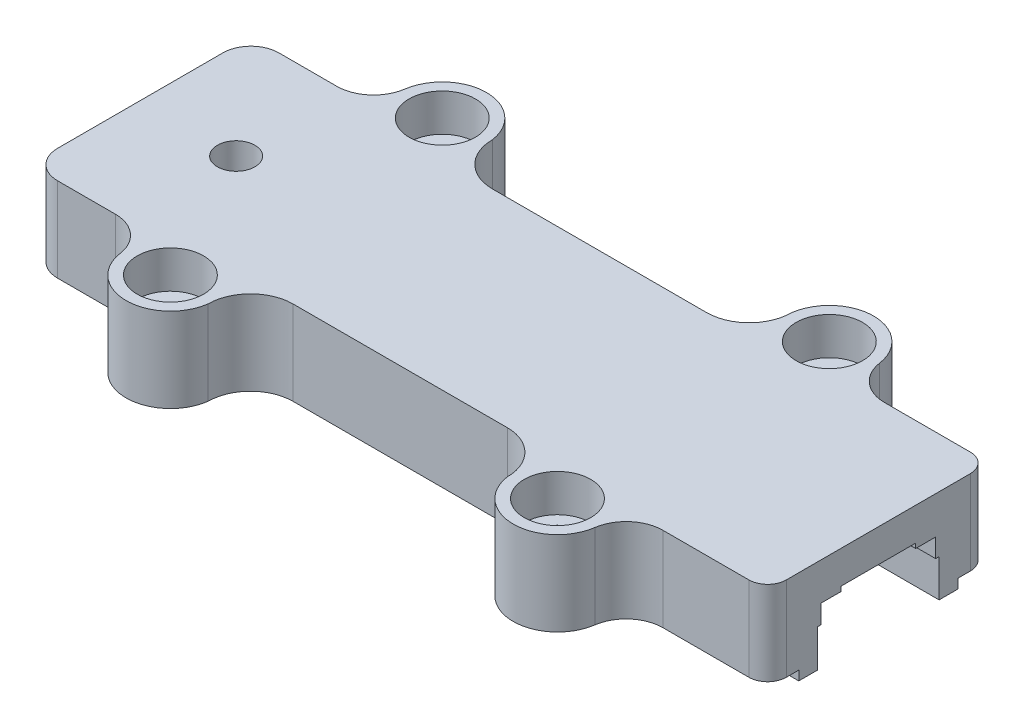
SolidWorks part; units mm, degrees
ref_plane "Front Plane" through (0, 0, 0) normal (0, 0, 1) x (1, 0, 0)
ref_plane "Top Plane" through (0, 0, 0) normal (0, 1, 0) x (1, 0, 0)
ref_plane "Right Plane" through (0, 0, 0) normal (1, 0, 0) x (0, 0, -1)
sketch "Sketch1" plane through (0, 0, 0) normal (0, 1, 0) x (1, 0, 0)
  line L1 (0, 15) -> (100, 15)
  line L2 (0, 15) -> (0, -15)
  line L3 (0, -15) -> (100, -15)
  line L4 (100, 15) -> (100, -15)
  point P4 (0, 0)
  dimension "D1" = 30
  dimension "D2" = 100
extrude "Boss-Extrude1" add sketch "Sketch1" along normal blind 12.7
sketch "Sketch2" plane through (100, 0, 0) normal (1, 0, 0) x (0, 0, -1)
  line L1 (-7.6, 0) -> (7.6, 0)
  line L2 (-7.6, 0) -> (-7.6, 7.62)
  line L3 (-7.6, 7.62) -> (7.6, 7.62)
  line L4 (7.6, 0) -> (7.6, 7.62)
  point P4 (0, 0)
  dimension "D1" = 15.2
  dimension "D2" = 7.62
extrude "Cut-Extrude1" cut sketch "Sketch2" against normal through all
sketch "Sketch3" plane through (100, 0, 0) normal (1, 0, 0) x (0, 0, -1)
  line L1 (-15, 0) -> (-7.6, 0) construction
  line L2 (7.6, 0) -> (15, 0) construction
  line L3 (-7.6, 0) -> (-8.235, 0)
  line L10 (7.6, 0) -> (7.6, 7.62) construction
  line L12 (7.6, 7.62) -> (-7.6, 7.62) construction
  line L13 (-7.6, 0) -> (-8.235, 0)
  line L14 (-7.6, 0) -> (-7.6, 5.08)
  line L15 (-7.6, 5.08) -> (-8.235, 5.08)
  line L16 (-8.235, 0) -> (-8.235, 5.08)
  line L17 (-7.6, 7.62) -> (-7.6, 0) construction
  line L18 (7.6, 0) -> (8.235, 0)
  line L19 (7.6, 0) -> (7.6, 5.08)
  line L20 (7.6, 5.08) -> (8.235, 5.08)
  line L21 (8.235, 0) -> (8.235, 5.08)
  line L22 (-5.06, 7.62) -> (5.06, 7.62)
  line L23 (-5.06, 7.62) -> (-5.06, 8.255)
  line L24 (-5.06, 8.255) -> (5.06, 8.255)
  line L25 (5.06, 7.62) -> (5.06, 8.255)
  line M1 (-15, 0) -> (-7.6, 0)
  line M2 (-7.6, 0) -> (-7.6, 7.62)
  line M3 (-7.6, 7.62) -> (7.6, 7.62)
  line M4 (7.6, 7.62) -> (7.6, 0)
  line M5 (7.6, 0) -> (15, 0)
  dimension "D5" = 0.635
  dimension "D6" = 2.54
  dimension "D7" = 0.635
  dimension "D8" = 2.54
  dimension "D9" = 0.635
  dimension "D10" = 2.54
  dimension "D11" = 2.54
extrude "Cut-Extrude2" cut sketch "Sketch3" against normal through all contours L16 L15 M1 M2 | L25 L24 L23 M3 | L21 L20 M5 M4
sketch "Sketch4" plane through (0, 0, 0) normal (0, -1, 0) x (1, 0, 0)
  line L1 (0, -8.235) -> (5, -8.235)
  line L2 (0, -8.235) -> (0, 8.235)
  line L3 (0, 8.235) -> (5, 8.235)
  line L4 (5, -8.235) -> (5, 8.235)
  line L5 (0, -8.235) -> (100, -8.235) construction
  line L6 (0, 8.235) -> (100, 8.235) construction
  dimension "D1" = 5
extrude "Boss-Extrude2" add sketch "Sketch4" against normal up to next
fillet "Fillet7" radius 1.5875 2 edges at (5, 6.35, -7.6) (5, 6.35, 7.6)
fillet "Fillet8" radius 1.5875 2 edges at (5, 2.54, -8.235) (5, 2.54, 8.235)
sketch "Sketch9" plane through (0, 7.62, 0) normal (0, -1, 0) x (1, 0, 0)
  line L0 (5, -5.06) -> (100, -5.06) construction
  line L1 (5, 5.06) -> (24.05, 5.06)
  line L2 (5, 5.06) -> (5, -5.06)
  line L3 (5, -5.06) -> (24.05, -5.06)
  line L4 (24.05, 5.06) -> (24.05, -5.06)
  dimension "D1" = 19.05
extrude "Boss-Extrude3" add sketch "Sketch9" against normal up to next
sketch "Sketch7" plane through (0, 7.62, 0) normal (0, -1, 0) x (1, 0, 0)
  line L0 (0, -15) -> (0, 15) construction
  line L1 (5, -6.0125) -> (5, 6.0125) construction
  circle A0 centre (13, 0) radius 2.54
  point P6 (0, 0)
  dimension "D1" = 5.08
  dimension "D2" = 8
extrude "Cut-Extrude4" cut sketch "Sketch7" against normal through all
sketch "Sketch10" plane through (0, 7.62, 0) normal (0, -1, 0) x (1, 0, 0)
  circle A0 centre (13, 0) radius 3.175
  circle A3 centre (13, 0) radius 2.54 construction
  dimension "D1" = 6.35
extrude "Cut-Extrude6" cut sketch "Sketch10" against normal blind 1.27
fillet "Fillet5" radius 1.5875 2 edges at (24.05, 7.9375, -5.06) (24.05, 7.9375, 5.06)
sketch "Sketch11" plane through (0, 12.7, 0) normal (0, 1, 0) x (1, 0, 0)
  line L0 (68.95, -15) -> (68.95, -18.415)
  line L1 (80.95, -15) -> (80.95, -18.415)
  line L4 (28.51, -18.415) -> (28.51, -15)
  line L5 (16.51, -15) -> (16.51, -18.415)
  line L8 (16.51, -15) -> (28.51, -15)
  line L9 (68.95, -15) -> (80.95, -15)
  line L13 (0, -15) -> (100, -15) construction
  arc A0 (69.0126, -19.2795) -> (80.8874, -19.2795) centre (74.95, -18.415) ccw construction
  arc A1 (16.5726, -19.2795) -> (28.4474, -19.2795) centre (22.51, -18.415) ccw construction
  arc A2 (16.51, -18.415) -> (28.51, -18.415) centre (22.51, -18.415) ccw
  arc A3 (68.95, -18.415) -> (80.95, -18.415) centre (74.95, -18.415) ccw
  dimension "D2" = 12
  dimension "D4" = 12
extrude "Boss-Extrude4" add sketch "Sketch11" against normal up to surface (12.7 mm away) up to face at (42.2517, 0, 0)
sketch "Sketch12" plane through (0, 12.7, 0) normal (0, 1, 0) x (1, 0, 0)
  circle A0 centre (22.51, -18.415) radius 4.5
  circle A1 centre (74.95, -18.415) radius 4.5
  dimension "D1" = 9
extrude "Cut-Extrude7" cut sketch "Sketch12" against normal blind 5.08
sketch "Sketch13" plane through (0, 7.62, 0) normal (0, 1, 0) x (1, 0, 0)
  circle A0 centre (22.51, -18.415) radius 2.75
  circle A1 centre (74.95, -18.415) radius 2.75
  dimension "D1" = 5.5
extrude "Cut-Extrude8" cut sketch "Sketch13" against normal through all
mirror "Mirror1" about plane through (0, 0, 0) normal (0, 0, 1) of "Boss-Extrude4", "Cut-Extrude7", "Cut-Extrude8"
fillet "Fillet6" radius 5 8 edges at (68.95, 6.35, 15) (80.95, 6.35, 15) (80.95, 6.35, -15) (68.95, 6.35, -15)
sketch "Sketch24" plane through (0, 0, 0) normal (0, -1, 0) x (1, 0, 0)
  line L0 (100, -10.775) -> (6.5875, -10.775)
  line L1 (2.46, -6.6475) -> (2.46, 6.6475)
  line L2 (6.5875, 10.775) -> (100, 10.775)
  line L12 (100, -15) -> (100, -8.235)
  line L13 (100, -8.235) -> (6.5875, -8.235)
  line L14 (5, -6.6475) -> (5, 6.6475)
  line L15 (6.5875, 8.235) -> (100, 8.235)
  line L16 (100, 8.235) -> (100, 15)
  line L17 (100, 15) -> (85.8352, 15)
  line L18 (64.0648, 15) -> (33.3952, 15)
  line L19 (11.6248, 15) -> (0, 15)
  line L20 (0, 15) -> (0, -15)
  line L21 (0, -15) -> (11.6248, -15)
  line L22 (33.3952, -15) -> (64.0648, -15)
  line L23 (85.8352, -15) -> (100, -15)
  line L24 (100, -15) -> (100, -10.775)
  line L25 (100, -8.235) -> (6.5875, -8.235) construction
  line L26 (5, -6.6475) -> (5, 6.6475) construction
  line L27 (6.5875, 8.235) -> (100, 8.235) construction
  line L28 (100, 10.775) -> (100, 15)
  line L29 (100, 15) -> (85.8352, 15)
  line L30 (64.0648, 15) -> (33.3952, 15)
  line L31 (11.6248, 15) -> (0, 15)
  line L32 (0, 15) -> (0, -15)
  line L33 (0, -15) -> (11.6248, -15)
  line L34 (33.3952, -15) -> (64.0648, -15)
  line L35 (85.8352, -15) -> (100, -15)
  arc A0 (2.46, -6.6475) -> (6.5875, -10.775) centre (6.5875, -6.6475) ccw
  arc A1 (6.5875, 10.775) -> (2.46, 6.6475) centre (6.5875, 6.6475) ccw
  arc A14 (5, -6.6475) -> (6.5875, -8.235) centre (6.5875, -6.6475) ccw
  arc A15 (6.5875, 8.235) -> (5, 6.6475) centre (6.5875, 6.6475) ccw
  arc A16 (80.8874, 19.2795) -> (85.8352, 15) centre (85.8352, 20) ccw
  arc A17 (80.8874, 19.2795) -> (69.0126, 19.2795) centre (74.95, 18.415) ccw
  arc A18 (64.0648, 15) -> (69.0126, 19.2795) centre (64.0648, 20) ccw
  arc A19 (28.4474, 19.2795) -> (33.3952, 15) centre (33.3952, 20) ccw
  arc A20 (28.4474, 19.2795) -> (16.5726, 19.2795) centre (22.51, 18.415) ccw
  arc A21 (11.6248, 15) -> (16.5726, 19.2795) centre (11.6248, 20) ccw
  arc A22 (16.5726, -19.2795) -> (11.6248, -15) centre (11.6248, -20) ccw
  arc A23 (16.5726, -19.2795) -> (28.4474, -19.2795) centre (22.51, -18.415) ccw
  arc A24 (33.3952, -15) -> (28.4474, -19.2795) centre (33.3952, -20) ccw
  arc A25 (69.0126, -19.2795) -> (64.0648, -15) centre (64.0648, -20) ccw
  arc A26 (69.0126, -19.2795) -> (80.8874, -19.2795) centre (74.95, -18.415) ccw
  arc A27 (85.8352, -15) -> (80.8874, -19.2795) centre (85.8352, -20) ccw
  arc A28 (5, -6.6475) -> (6.5875, -8.235) centre (6.5875, -6.6475) ccw construction
  arc A29 (6.5875, 8.235) -> (5, 6.6475) centre (6.5875, 6.6475) ccw construction
  arc A30 (80.8874, 19.2795) -> (85.8352, 15) centre (85.8352, 20) ccw
  arc A31 (80.8874, 19.2795) -> (69.0126, 19.2795) centre (74.95, 18.415) ccw
  arc A32 (64.0648, 15) -> (69.0126, 19.2795) centre (64.0648, 20) ccw
  arc A33 (28.4474, 19.2795) -> (33.3952, 15) centre (33.3952, 20) ccw
  arc A34 (28.4474, 19.2795) -> (16.5726, 19.2795) centre (22.51, 18.415) ccw
  arc A35 (11.6248, 15) -> (16.5726, 19.2795) centre (11.6248, 20) ccw
  arc A36 (16.5726, -19.2795) -> (11.6248, -15) centre (11.6248, -20) ccw
  arc A37 (16.5726, -19.2795) -> (28.4474, -19.2795) centre (22.51, -18.415) ccw
  arc A38 (33.3952, -15) -> (28.4474, -19.2795) centre (33.3952, -20) ccw
  arc A39 (69.0126, -19.2795) -> (64.0648, -15) centre (64.0648, -20) ccw
  arc A40 (69.0126, -19.2795) -> (80.8874, -19.2795) centre (74.95, -18.415) ccw
  arc A41 (85.8352, -15) -> (80.8874, -19.2795) centre (85.8352, -20) ccw
  dimension "D3" = 21.55
  dimension "D1" = 0
  dimension "D2" = 2.54
extrude "Cut-Extrude9" cut sketch "Sketch24" against normal blind 1.27
sketch "Sketch25" plane through (0, 7.62, 0) normal (0, -1, 0) x (1, 0, 0)
  line L0 (27.86, 6.3669) -> (27.86, 0.436) construction
  line L1 (5, -6.6475) -> (5, 6.6475) construction
  line L2 (6.5875, 7.6) -> (100, 7.6) construction
  line L3 (24.685, 7.6) -> (27.86, 7.6)
  line L4 (24.685, 7.6) -> (24.685, 5.06)
  line L5 (24.685, 5.06) -> (27.86, 5.06)
  line L6 (27.86, 7.6) -> (27.86, 5.06)
  line L7 (25.6375, 5.06) -> (100, 5.06) construction
  line L8 (6.5875, -7.6) -> (100, -7.6) construction
  line L9 (24.685, -7.6) -> (27.86, -7.6)
  line L10 (24.685, -7.6) -> (24.685, -5.06)
  line L11 (24.685, -5.06) -> (27.86, -5.06)
  line L12 (27.86, -7.6) -> (27.86, -5.06)
  line L13 (25.6375, -5.06) -> (100, -5.06) construction
  dimension "D1" = 22.86
  dimension "D2" = 3.175
extrude "Boss-Extrude5" add sketch "Sketch25" along normal blind 2.54
sketch "Sketch26" plane through (24.685, 0, 0) normal (-1, 0, 0) x (0, 0, 1)
  line L0 (7.6, 7.62) -> (5.06, 7.62) construction
  line L1 (5.06, 7.62) -> (5.06, 5.08) construction
  line L2 (5.06, 5.08) -> (7.6, 5.08) construction
  line L3 (7.6, 5.08) -> (7.6, 7.62) construction
  line L4 (-5.06, 7.62) -> (-7.6, 7.62) construction
  line L5 (-7.6, 7.62) -> (-7.6, 5.08) construction
  line L6 (-7.6, 5.08) -> (-5.06, 5.08) construction
  line L7 (-5.06, 5.08) -> (-5.06, 7.62) construction
  line L8 (7.6, 7.62) -> (5.06, 7.62)
  line L9 (5.06, 7.62) -> (5.06, 5.08)
  line L10 (5.06, 5.08) -> (7.6, 5.08)
  line L11 (7.6, 5.08) -> (7.6, 7.62)
  line L12 (-5.06, 7.62) -> (-7.6, 7.62)
  line L13 (-7.6, 7.62) -> (-7.6, 5.08)
  line L14 (-7.6, 5.08) -> (-5.06, 5.08)
  line L15 (-5.06, 5.08) -> (-5.06, 7.62)
extrude "Boss-Extrude6" add sketch "Sketch26" along normal up to next
sketch "Sketch31" plane through (100, 0, 0) normal (1, 0, 0) x (0, 0, -1)
  line L2 (7.6, 5.08) -> (7.7651, 5.08)
  line L3 (7.6, 5.08) -> (7.6, 7.62)
  line L4 (7.6, 7.62) -> (7.7651, 7.62)
  line L5 (7.7651, 5.08) -> (7.7651, 7.62)
  line L6 (-7.6, 5.08) -> (-7.7651, 5.08)
  line L7 (-7.6, 5.08) -> (-7.6, 7.62)
  line L8 (-7.6, 7.62) -> (-7.7651, 7.62)
  line L9 (-7.7651, 5.08) -> (-7.7651, 7.62)
  dimension "D1" = 0.1651
  dimension "D2" = 0.1651
extrude "adjust" cut sketch "Sketch31" against normal up to surface (72.14 mm away) up to face at (27.86, 6.35, -6.33)
fillet "Fillet9" radius 1.5875 4 edges at (5, 6.35, -5.06) (5, 6.35, 5.06) (27.86, 6.35, 7.7651) (27.86, 6.35, -7.7651)
sketch "Sketch27" plane through (0, 0, 0) normal (0, 1, 0) x (1, 0, 0)
  line L1 (-5.3987, 25.4) -> (108.9013, 25.4)
  line L2 (-5.3987, 25.4) -> (-5.3987, -25.4)
  line L3 (-5.3987, -25.4) -> (108.9013, -25.4)
  line L4 (108.9013, 25.4) -> (108.9013, -25.4)
  point P4 (-5.3987, 0)
  dimension "D1" = 50.8
  dimension "D2" = 114.3
sketch "Sketch28" plane through (0, 0, 0) normal (0, -1, 0) x (1, 0, 0)
  line L0 (0, 0) -> (-2.8235, 0) construction
sketch "Sketch32" plane through (0, 12.7, 0) normal (0, 1, 0) x (1, 0, 0)
  line L3 (100, -10.775) -> (100, -15) construction
sketch "Sketch33" plane through (0, 1.27, 0) normal (0, -1, 0) x (1, 0, 0)
  line L0 (28.4474, 19.2795) -> (28.4474, 29.295)
  line L1 (28.4474, 29.295) -> (69.0126, 29.295)
  line L2 (69.0126, 29.295) -> (69.0126, 19.2795)
  line L3 (34.2269, 13.5) -> (63.2331, 13.5)
  line L4 (64.0648, 15) -> (33.3952, 15) construction
  line L5 (0, 0) -> (114.5376, 0) construction
  line L6 (28.4474, -19.2795) -> (28.4474, -29.295)
  line L7 (34.2269, -13.5) -> (63.2331, -13.5)
  line L8 (69.0126, -29.295) -> (69.0126, -19.2795)
  line L9 (28.4474, -29.295) -> (69.0126, -29.295)
  arc A0 (69.0126, 19.2795) -> (63.2331, 13.5) centre (63.2331, 19.2795) cw
  arc A1 (28.4474, 19.2795) -> (34.2269, 13.5) centre (34.2269, 19.2795) ccw
  arc A2 (28.4474, -19.2795) -> (34.2269, -13.5) centre (34.2269, -19.2795) cw
  arc A3 (69.0126, -19.2795) -> (63.2331, -13.5) centre (63.2331, -19.2795) ccw
  dimension "D1" = 1.5
extrude "Cut-Extrude10" cut sketch "Sketch33" against normal through all
fillet "Fillet10" radius 3.81 2 edges at (0, 6.985, 15) (0, 6.985, -15)
fillet "Fillet11" radius 2.54 2 edges at (100, 6.985, 15) (100, 6.985, -15)
sketch "Sketch34" plane through (0, 12.7, 0) normal (0, 1, 0) x (1, 0, 0)
  line L8 (85.8352, -15) -> (97.46, -15)
  line L9 (100, -12.46) -> (100, 12.46)
  line L10 (97.46, 15) -> (85.8352, 15)
  line L11 (63.2331, 13.5) -> (34.2269, 13.5)
  line L12 (11.6248, 15) -> (3.81, 15)
  line L13 (0, 11.19) -> (0, -11.19)
  line L14 (3.81, -15) -> (11.6248, -15)
  line L15 (34.2269, -13.5) -> (63.2331, -13.5)
  line L16 (85.8352, -15) -> (97.46, -15)
  line L17 (100, -12.46) -> (100, 12.46)
  line L18 (97.46, 15) -> (85.8352, 15)
  line L19 (63.2331, 13.5) -> (34.2269, 13.5)
  line L20 (11.6248, 15) -> (3.81, 15)
  line L21 (0, 11.19) -> (0, -11.19)
  line L22 (3.81, -15) -> (11.6248, -15)
  line L23 (34.2269, -13.5) -> (63.2331, -13.5)
  arc A16 (97.46, -15) -> (100, -12.46) centre (97.46, -12.46) ccw
  arc A17 (100, 12.46) -> (97.46, 15) centre (97.46, 12.46) ccw
  arc A18 (80.8874, 19.2795) -> (85.8352, 15) centre (85.8352, 20) ccw
  arc A19 (80.8874, 19.2795) -> (69.0126, 19.2795) centre (74.95, 18.415) ccw
  arc A20 (63.2331, 13.5) -> (69.0126, 19.2795) centre (63.2331, 19.2795) ccw
  arc A21 (28.4474, 19.2795) -> (34.2269, 13.5) centre (34.2269, 19.2795) ccw
  arc A22 (28.4474, 19.2795) -> (16.5726, 19.2795) centre (22.51, 18.415) ccw
  arc A23 (11.6248, 15) -> (16.5726, 19.2795) centre (11.6248, 20) ccw
  arc A24 (3.81, 15) -> (0, 11.19) centre (3.81, 11.19) ccw
  arc A25 (0, -11.19) -> (3.81, -15) centre (3.81, -11.19) ccw
  arc A26 (16.5726, -19.2795) -> (11.6248, -15) centre (11.6248, -20) ccw
  arc A27 (16.5726, -19.2795) -> (28.4474, -19.2795) centre (22.51, -18.415) ccw
  arc A28 (34.2269, -13.5) -> (28.4474, -19.2795) centre (34.2269, -19.2795) ccw
  arc A29 (69.0126, -19.2795) -> (63.2331, -13.5) centre (63.2331, -19.2795) ccw
  arc A30 (69.0126, -19.2795) -> (80.8874, -19.2795) centre (74.95, -18.415) ccw
  arc A31 (85.8352, -15) -> (80.8874, -19.2795) centre (85.8352, -20) ccw
  arc A32 (97.46, -15) -> (100, -12.46) centre (97.46, -12.46) ccw
  arc A33 (100, 12.46) -> (97.46, 15) centre (97.46, 12.46) ccw
  arc A34 (80.8874, 19.2795) -> (85.8352, 15) centre (85.8352, 20) ccw
  arc A35 (80.8874, 19.2795) -> (69.0126, 19.2795) centre (74.95, 18.415) ccw
  arc A36 (63.2331, 13.5) -> (69.0126, 19.2795) centre (63.2331, 19.2795) ccw
  arc A37 (28.4474, 19.2795) -> (34.2269, 13.5) centre (34.2269, 19.2795) ccw
  arc A38 (28.4474, 19.2795) -> (16.5726, 19.2795) centre (22.51, 18.415) ccw
  arc A39 (11.6248, 15) -> (16.5726, 19.2795) centre (11.6248, 20) ccw
  arc A40 (3.81, 15) -> (0, 11.19) centre (3.81, 11.19) ccw
  arc A41 (0, -11.19) -> (3.81, -15) centre (3.81, -11.19) ccw
  arc A42 (16.5726, -19.2795) -> (11.6248, -15) centre (11.6248, -20) ccw
  arc A43 (16.5726, -19.2795) -> (28.4474, -19.2795) centre (22.51, -18.415) ccw
  arc A44 (34.2269, -13.5) -> (28.4474, -19.2795) centre (34.2269, -19.2795) ccw
  arc A45 (69.0126, -19.2795) -> (63.2331, -13.5) centre (63.2331, -19.2795) ccw
  arc A46 (69.0126, -19.2795) -> (80.8874, -19.2795) centre (74.95, -18.415) ccw
  arc A47 (85.8352, -15) -> (80.8874, -19.2795) centre (85.8352, -20) ccw
  dimension "D1" = 0
sketch "Sketch37" plane through (0, 1.27, 0) normal (0, -1, 0) x (1, 0, 0)
  line L12 (100, 10.775) -> (100, 12.46)
  line L13 (97.46, 15) -> (85.8352, 15)
  line L14 (63.2331, 13.5) -> (34.2269, 13.5)
  line L15 (11.6248, 15) -> (3.81, 15)
  line L16 (0, 11.19) -> (0, -11.19)
  line L17 (3.81, -15) -> (11.6248, -15)
  line L18 (34.2269, -13.5) -> (63.2331, -13.5)
  line L19 (85.8352, -15) -> (97.46, -15)
  line L20 (100, -12.46) -> (100, -10.775)
  line L21 (100, -10.775) -> (6.5875, -10.775)
  line L22 (2.46, -6.6475) -> (2.46, 6.6475)
  line L23 (6.5875, 10.775) -> (100, 10.775)
  line L24 (100, 10.775) -> (100, 12.46)
  line L25 (97.46, 15) -> (85.8352, 15)
  line L26 (63.2331, 13.5) -> (34.2269, 13.5)
  line L27 (11.6248, 15) -> (3.81, 15)
  line L28 (0, 11.19) -> (0, -11.19)
  line L29 (3.81, -15) -> (11.6248, -15)
  line L30 (34.2269, -13.5) -> (63.2331, -13.5)
  line L31 (85.8352, -15) -> (97.46, -15)
  line L32 (100, -12.46) -> (100, -10.775)
  line L33 (100, -10.775) -> (6.5875, -10.775)
  line L34 (2.46, -6.6475) -> (2.46, 6.6475)
  line L35 (6.5875, 10.775) -> (100, 10.775)
  arc A18 (100, 12.46) -> (97.46, 15) centre (97.46, 12.46) ccw
  arc A19 (80.8874, 19.2795) -> (85.8352, 15) centre (85.8352, 20) ccw
  arc A20 (80.8874, 19.2795) -> (69.0126, 19.2795) centre (74.95, 18.415) ccw
  arc A21 (63.2331, 13.5) -> (69.0126, 19.2795) centre (63.2331, 19.2795) ccw
  arc A22 (28.4474, 19.2795) -> (34.2269, 13.5) centre (34.2269, 19.2795) ccw
  arc A23 (28.4474, 19.2795) -> (16.5726, 19.2795) centre (22.51, 18.415) ccw
  arc A24 (11.6248, 15) -> (16.5726, 19.2795) centre (11.6248, 20) ccw
  arc A25 (3.81, 15) -> (0, 11.19) centre (3.81, 11.19) ccw
  arc A26 (0, -11.19) -> (3.81, -15) centre (3.81, -11.19) ccw
  arc A27 (16.5726, -19.2795) -> (11.6248, -15) centre (11.6248, -20) ccw
  arc A28 (16.5726, -19.2795) -> (28.4474, -19.2795) centre (22.51, -18.415) ccw
  arc A29 (34.2269, -13.5) -> (28.4474, -19.2795) centre (34.2269, -19.2795) ccw
  arc A30 (69.0126, -19.2795) -> (63.2331, -13.5) centre (63.2331, -19.2795) ccw
  arc A31 (69.0126, -19.2795) -> (80.8874, -19.2795) centre (74.95, -18.415) ccw
  arc A32 (85.8352, -15) -> (80.8874, -19.2795) centre (85.8352, -20) ccw
  arc A33 (97.46, -15) -> (100, -12.46) centre (97.46, -12.46) ccw
  arc A34 (2.46, -6.6475) -> (6.5875, -10.775) centre (6.5875, -6.6475) ccw
  arc A35 (6.5875, 10.775) -> (2.46, 6.6475) centre (6.5875, 6.6475) ccw
  arc A36 (100, 12.46) -> (97.46, 15) centre (97.46, 12.46) ccw
  arc A37 (80.8874, 19.2795) -> (85.8352, 15) centre (85.8352, 20) ccw
  arc A38 (80.8874, 19.2795) -> (69.0126, 19.2795) centre (74.95, 18.415) ccw
  arc A39 (63.2331, 13.5) -> (69.0126, 19.2795) centre (63.2331, 19.2795) ccw
  arc A40 (28.4474, 19.2795) -> (34.2269, 13.5) centre (34.2269, 19.2795) ccw
  arc A41 (28.4474, 19.2795) -> (16.5726, 19.2795) centre (22.51, 18.415) ccw
  arc A42 (11.6248, 15) -> (16.5726, 19.2795) centre (11.6248, 20) ccw
  arc A43 (3.81, 15) -> (0, 11.19) centre (3.81, 11.19) ccw
  arc A44 (0, -11.19) -> (3.81, -15) centre (3.81, -11.19) ccw
  arc A45 (16.5726, -19.2795) -> (11.6248, -15) centre (11.6248, -20) ccw
  arc A46 (16.5726, -19.2795) -> (28.4474, -19.2795) centre (22.51, -18.415) ccw
  arc A47 (34.2269, -13.5) -> (28.4474, -19.2795) centre (34.2269, -19.2795) ccw
  arc A48 (69.0126, -19.2795) -> (63.2331, -13.5) centre (63.2331, -19.2795) ccw
  arc A49 (69.0126, -19.2795) -> (80.8874, -19.2795) centre (74.95, -18.415) ccw
  arc A50 (85.8352, -15) -> (80.8874, -19.2795) centre (85.8352, -20) ccw
  arc A51 (97.46, -15) -> (100, -12.46) centre (97.46, -12.46) ccw
  arc A52 (2.46, -6.6475) -> (6.5875, -10.775) centre (6.5875, -6.6475) ccw
  arc A53 (6.5875, 10.775) -> (2.46, 6.6475) centre (6.5875, 6.6475) ccw
  dimension "D1" = 0
sketch "Sketch40" plane through (0, 7.62, 0) normal (0, -1, 0) x (1, 0, 0)
  line L0 (100, 7.7651) -> (29.4475, 7.7651)
  line L1 (29.4475, 7.7651) -> (100, 7.7651) construction
  line L2 (27.86, 6.1776) -> (27.86, 5.06)
  line L3 (27.86, -5.06) -> (27.86, -6.1776)
  line L4 (29.4475, -7.7651) -> (100, -7.7651)
  arc A0 (29.4475, 7.7651) -> (27.86, 6.1776) centre (29.4475, 6.1776) ccw
  arc A1 (27.86, -6.1776) -> (29.4475, -7.7651) centre (29.4475, -6.1776) ccw
sketch "Sketch35" plane through (0, 5.08, 0) normal (0, -1, 0) x (1, 0, 0)
  line L8 (100, 8.235) -> (100, 10.775)
  line L9 (100, 10.775) -> (6.5875, 10.775)
  line L10 (2.46, 6.6475) -> (2.46, -6.6475)
  line L11 (6.5875, -10.775) -> (100, -10.775)
  line L12 (100, -10.775) -> (100, -8.235)
  line L13 (100, -8.235) -> (6.5875, -8.235)
  line L14 (5, -6.6475) -> (5, 6.6475)
  line L15 (6.5875, 8.235) -> (100, 8.235)
  line L21 (100, -8.235) -> (6.5875, -8.235)
  line L22 (5, -6.6475) -> (5, 6.6475)
  line L23 (6.5875, 8.235) -> (100, 8.235)
  arc A4 (6.5875, 10.775) -> (2.46, 6.6475) centre (6.5875, 6.6475) ccw
  arc A5 (2.46, -6.6475) -> (6.5875, -10.775) centre (6.5875, -6.6475) ccw
  arc A6 (5, -6.6475) -> (6.5875, -8.235) centre (6.5875, -6.6475) ccw
  arc A7 (6.5875, 8.235) -> (5, 6.6475) centre (6.5875, 6.6475) ccw
  arc A10 (5, -6.6475) -> (6.5875, -8.235) centre (6.5875, -6.6475) ccw
  arc A11 (6.5875, 8.235) -> (5, 6.6475) centre (6.5875, 6.6475) ccw
  dimension "D1" = 0
sketch "Sketch41" plane through (0, 7.62, 0) normal (0, -1, 0) x (1, 0, 0)
  line L0 (27.86, 5.06) -> (27.86, 6.1776) construction
  line L1 (29.4475, 7.7651) -> (100, 7.7651) construction
  line L5 (6.5875, 5.06) -> (27.86, 5.06) construction
  line L6 (100, -7.7651) -> (29.4475, -7.7651) construction
  line L7 (27.86, -6.1776) -> (27.86, -5.06) construction
  line L8 (27.86, -5.06) -> (6.5875, -5.06) construction
  line L12 (27.86, 5.06) -> (27.86, 6.1776)
  line L13 (29.4475, 7.7651) -> (100, 7.7651)
  line L14 (5, -3.4725) -> (5, 3.4725)
  line L17 (6.5875, 5.06) -> (27.86, 5.06)
  line L18 (100, -7.7651) -> (29.4475, -7.7651)
  line L19 (27.86, -6.1776) -> (27.86, -5.06)
  line L20 (27.86, -5.06) -> (6.5875, -5.06)
  arc A0 (29.4475, 7.7651) -> (27.86, 6.1776) centre (29.4475, 6.1776) ccw construction
  arc A2 (6.5875, 5.06) -> (5, 3.4725) centre (6.5875, 3.4725) ccw construction
  arc A3 (27.86, -6.1776) -> (29.4475, -7.7651) centre (29.4475, -6.1776) ccw construction
  arc A4 (5, -3.4725) -> (6.5875, -5.06) centre (6.5875, -3.4725) ccw construction
  arc A6 (29.4475, 7.7651) -> (27.86, 6.1776) centre (29.4475, 6.1776) ccw
  arc A8 (6.5875, 5.06) -> (5, 3.4725) centre (6.5875, 3.4725) ccw
  arc A9 (27.86, -6.1776) -> (29.4475, -7.7651) centre (29.4475, -6.1776) ccw
  arc A10 (5, -3.4725) -> (6.5875, -5.06) centre (6.5875, -3.4725) ccw
sketch "Sketch36" plane through (0, 8.255, 0) normal (0, -1, 0) x (1, 0, 0)
  line L4 (24.05, 3.4725) -> (24.05, -3.4725)
  line L5 (25.6375, -5.06) -> (100, -5.06)
  line L6 (100, -5.06) -> (100, 5.06)
  line L7 (100, 5.06) -> (25.6375, 5.06)
  line L8 (24.05, 3.4725) -> (24.05, -3.4725)
  line L9 (25.6375, -5.06) -> (100, -5.06)
  line L11 (100, 5.06) -> (25.6375, 5.06)
  arc A2 (24.05, -3.4725) -> (25.6375, -5.06) centre (25.6375, -3.4725) ccw
  arc A3 (25.6375, 5.06) -> (24.05, 3.4725) centre (25.6375, 3.4725) ccw
  arc A4 (24.05, -3.4725) -> (25.6375, -5.06) centre (25.6375, -3.4725) ccw
  arc A5 (25.6375, 5.06) -> (24.05, 3.4725) centre (25.6375, 3.4725) ccw
  dimension "D1" = 0
sketch "Sketch43" plane through (0, 12.7, 0) normal (0, 1, 0) x (1, 0, 0)
  line L0 (91.0565, 10.775) -> (0, 10.775) construction
  line L1 (100, 10.775) -> (6.5875, 10.775) construction
  line L2 (0, 10.775) -> (0, 15) construction
  line L3 (0, 11.19) -> (0, -11.19) construction
equation "\"D11@Sketch3\"=\"D10@Sketch3\""
equation "\"D6@Sketch3\"=\"D10@Sketch3\""
equation "\"D8@Sketch3\"=\"D10@Sketch3\""
equation "\"D9@Sketch3\" = \"D5@Sketch3\""
equation "\"D7@Sketch3\"=\"D5@Sketch3\""
